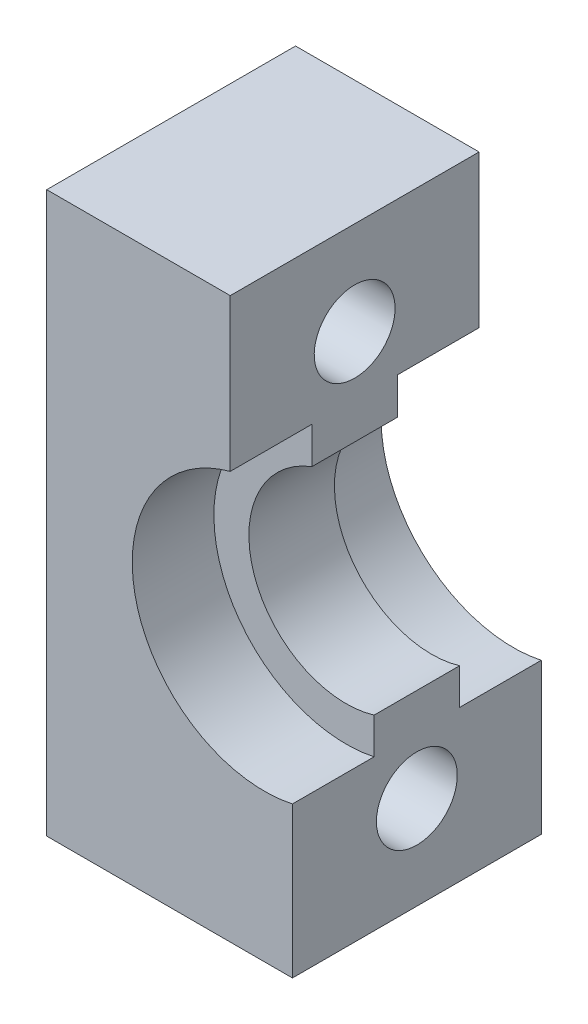
SolidWorks part; units mm, degrees
ref_plane "Front Plane" through (0, 0, 0) normal (0, 0, 1) x (1, 0, 0)
ref_plane "Top Plane" through (0, 0, 0) normal (0, 1, 0) x (1, 0, 0)
ref_plane "Right Plane" through (0, 0, 0) normal (1, 0, 0) x (0, 0, -1)
sketch "Sketch3" plane through (0, 0, 0) normal (0, 0, 1) x (1, 0, 0)
  line L0 (0, -18) -> (0, 18)
  line L1 (0, 18) -> (11.8, 18)
  line L2 (0, -18) -> (15.8, -18)
  line L3 (8.69, 0) -> (-8.69, 0) construction
  line L4 (0, -11) -> (0, 11) construction
  line L5 (11.8, 18) -> (11.8, 8.2104)
  line L6 (15.8, -18) -> (15.8, -8.3072)
  arc A0 (11.8, 8.2104) -> (15.8, -8.3072) centre (14, 0) ccw
  dimension "D1" = 17
  dimension "D2" = 36
  dimension "D3" = 18
  dimension "D4" = 14
  dimension "D5" = 11.8
  dimension "D6" = 15.8
extrude "Boss-Extrude2" add sketch "Sketch3" along normal mid plane 16
sketch "Sketch4" plane through (0, 0, 0) normal (0, 0, 1) x (1, 0, 0)
  line L0 (11.8, 8.2104) -> (11.8, 5.85)
  line L1 (15.8, -5.9852) -> (15.8, -8.3072)
  arc A0 (11.8, 5.85) -> (15.8, -5.9852) centre (14, 0) ccw
  arc A1 (11.8, 8.2104) -> (15.8, -8.3072) centre (14, 0) ccw
  dimension "D1" = 12.5
  dimension "D2" = 17
  dimension "D3" = 2.2
  dimension "D4" = 1.8
extrude "Boss-Extrude3" add sketch "Sketch4" along normal mid plane 5.5
sketch "Sketch5" plane through (0, 0, 0) normal (1, 0, 0) x (0, 0, -1)
  line L0 (0, 8.69) -> (0, -8.69) construction
  line L1 (8.69, 0) -> (-8.69, 0) construction
  circle A0 centre (0, 12) radius 2.6
  circle A1 centre (0, -12) radius 2.6
  dimension "D1" = 5.2
  dimension "D2" = 5.2
  dimension "D3" = 12
  dimension "D4" = 12
extrude "Cut-Extrude1" cut sketch "Sketch5" along normal up to next
